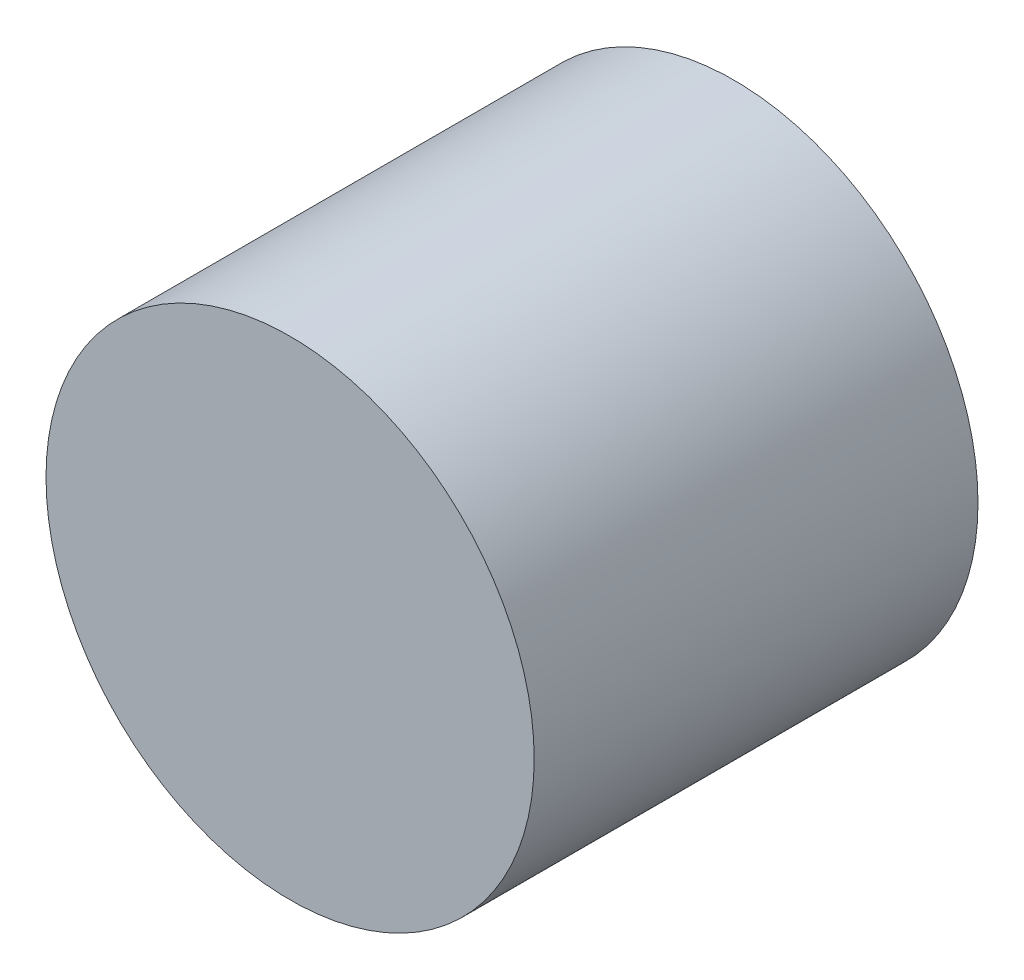
SolidWorks part; units mm, degrees
ref_plane "Plan de face" through (0, 0, 0) normal (0, 0, 1) x (1, 0, 0)
ref_plane "Plan de dessus" through (0, 0, 0) normal (0, 1, 0) x (1, 0, 0)
ref_plane "Plan de droite" through (0, 0, 0) normal (1, 0, 0) x (0, 0, -1)
sketch "Esquisse1" plane through (0, 0, 0) normal (0, 0, 1) x (1, 0, 0)
  circle A0 centre (0, 0) radius 220
  dimension "D1" = 440
extrude "Boss.-Extru.1" add sketch "Esquisse1" along normal blind 400
